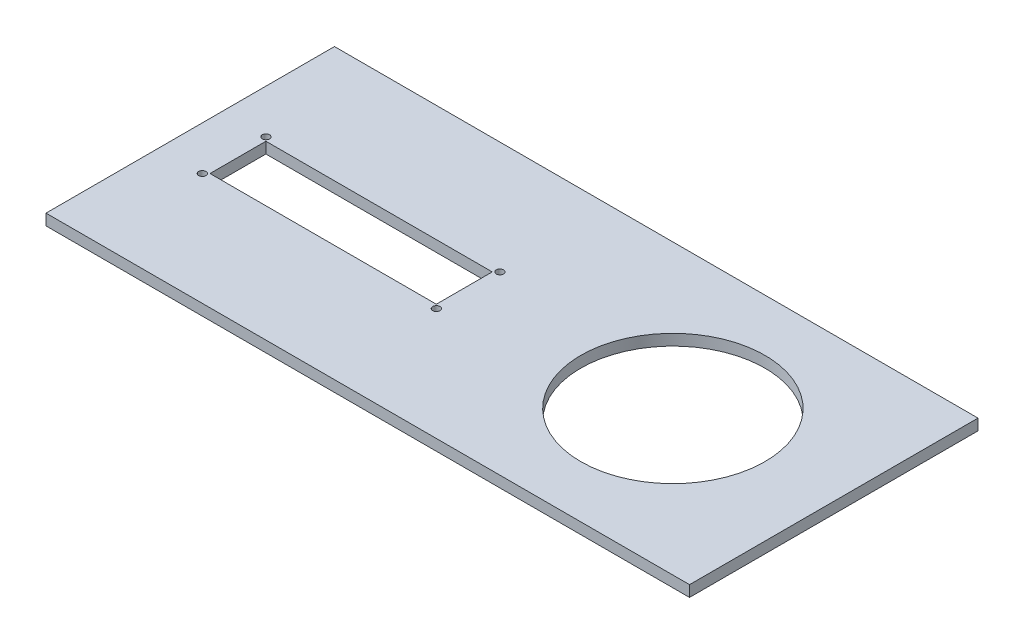
SolidWorks part; units mm, degrees
ref_plane "Front Plane" through (0, 0, 0) normal (0, 0, 1) x (1, 0, 0)
ref_plane "Top Plane" through (0, 0, 0) normal (0, 1, 0) x (1, 0, 0)
ref_plane "Right Plane" through (0, 0, 0) normal (1, 0, 0) x (0, 0, -1)
sketch "Sketch1" plane through (0, 0, 0) normal (0, 1, 0) x (1, 0, 0)
  line L1 (-184.15, -82.55) -> (184.15, -82.55)
  line L2 (-184.15, -82.55) -> (-184.15, 82.55)
  line L3 (-184.15, 82.55) -> (184.15, 82.55)
  line L4 (184.15, -82.55) -> (184.15, 82.55)
  line L5 (-184.15, -82.55) -> (184.15, 82.55) construction
  line L6 (-184.15, 82.55) -> (184.15, -82.55) construction
  point P0 (0, 0)
  dimension "D1" = 165.1
  dimension "D2" = 368.3
extrude "Boss-Extrude1" add sketch "Sketch1" along normal blind 6.35
sketch "Sketch2" plane through (0, 6.35, 0) normal (0, 1, 0) x (1, 0, 0)
  line L0 (184.15, 82.55) -> (0, -82.55) construction
  line L1 (184.15, 82.55) -> (-184.15, 82.55) construction
  line L2 (-184.15, 0) -> (184.15, 0) construction
  line L7 (-156.845, 16.002) -> (-27.305, 16.002)
  line L8 (-156.845, 16.002) -> (-156.845, -16.002)
  line L9 (-156.845, -16.002) -> (-27.305, -16.002)
  line L10 (-27.305, 16.002) -> (-27.305, -16.002)
  line L11 (-156.845, 16.002) -> (-27.305, -16.002) construction
  line L12 (-156.845, -16.002) -> (-27.305, 16.002) construction
  line L13 (-184.15, 82.55) -> (-184.15, -82.55) construction
  line L14 (184.15, -82.55) -> (184.15, 82.55) construction
  line L15 (-184.15, -82.55) -> (184.15, -82.55) construction
  line L16 (0, 82.55) -> (184.15, -82.55) construction
  line L17 (0, 82.55) -> (-184.15, -82.55) construction
  line L18 (0, -82.55) -> (-184.15, 82.55) construction
  circle A0 centre (92.075, 0) radius 52.705
  circle A1 centre (92.075, 0) radius 76.2 construction
  point P6 (0, 0)
  point P7 (-92.075, 0)
  point P23 (0, 0)
  point P41 (-646.5654, 161.391)
  line B0 (-156.845, -16.002) -> (-27.305, -16.002) construction
  line B1 (-156.845, -16.002) -> (-156.845, 16.002) construction
  line B2 (-156.845, 16.002) -> (-27.305, 16.002) construction
  line B3 (-27.305, -16.002) -> (-27.305, 16.002) construction
  line B4 (-156.845, -16.002) -> (-27.305, 16.002) construction
  line B5 (-156.845, 16.002) -> (-27.305, -16.002) construction
  circle B6 centre (-159.0294, 18.1864) radius 2.0828
  circle B7 centre (-159.0294, -18.1864) radius 2.0828
  circle B8 centre (-25.1206, 18.1864) radius 2.0828
  circle B9 centre (-25.1206, -18.1864) radius 2.0828
  dimension "D1" = 105.41
  dimension "D4" = 152.4
  dimension "D2" = 129.54
  dimension "D3" = 32.004
sketch_block_instance "Block1-1"
sketch_block "Block1" parameters "D3"=4.1656, "D1"=32.004, "D2"=129.54
extrude "Cut-Extrude1" cut sketch "Sketch2" against normal through all
